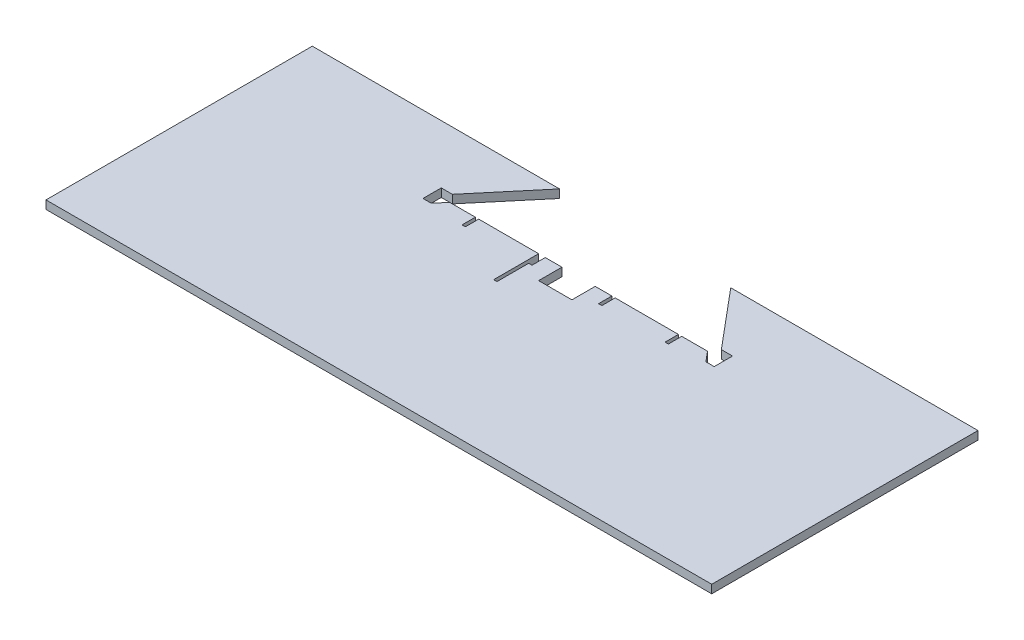
SolidWorks part; units mm, degrees
material "Depron"
ref_plane "Front Plane" through (0, 0, 0) normal (0, 0, 1) x (1, 0, 0)
ref_plane "Top Plane" through (0, 0, 0) normal (0, 1, 0) x (1, 0, 0)
ref_plane "Right Plane" through (0, 0, 0) normal (1, 0, 0) x (0, 0, -1)
sketch "Sketch1" plane through (0, 0, 0) normal (0, 1, 0) x (1, 0, 0)
  line L0 (32.6619, 101.6) -> (127, 101.6)
  line L1 (-127, 0) -> (127, 0)
  line L2 (-127, 0) -> (-127, 101.6)
  line L3 (-127, 101.6) -> (-32.6619, 101.6)
  line L4 (127, 0) -> (127, 101.6)
  line L5 (0, -898.4) -> (0, 49101.6) construction
  line L6 (-53.975, 76.2) -> (-32.6619, 101.6)
  line L7 (-53.975, 76.2) -> (53.975, 76.2)
  line L8 (53.975, 76.2) -> (32.6619, 101.6)
  line L9 (-1003.9539, 76.2) -> (48996.0461, 76.2) construction
  point P11 (0, 76.2)
  dimension "D1" = 101.6
  dimension "D2" = 254
  dimension "D4" = 107.95
  dimension "D6" = 25.4
extrude "Boss-Extrude1" add sketch "Sketch1" along normal blind 3.175
sketch "Sketch2" plane through (0, 3.175, 0) normal (0, 1, 0) x (-1, 0, 0)
  line L0 (0, 0) -> (0, -134.62) construction
  line L1 (127, 0) -> (-127, 0) construction
  line L2 (-53.975, -76.2) -> (53.975, -76.2) construction
  line L3 (39.37, -76.2) -> (38.1, -76.2)
  line L4 (39.37, -76.2) -> (39.37, -71.12)
  line L5 (39.37, -71.12) -> (38.1, -71.12)
  line L6 (38.1, -76.2) -> (38.1, -71.12)
  line L7 (13.97, -76.2) -> (12.7, -76.2)
  line L8 (-53.975, -76.2) -> (53.975, -76.2) construction
  line L9 (13.97, -71.12) -> (12.7, -71.12)
  line L10 (12.7, -76.2) -> (12.7, -71.12)
  line L11 (-12.7, -76.2) -> (-12.7, -71.12)
  line L12 (-13.97, -71.12) -> (-12.7, -71.12)
  line L13 (-13.97, -76.2) -> (-13.97, -71.12)
  line L14 (-13.97, -76.2) -> (-12.7, -76.2)
  line L15 (-38.1, -76.2) -> (-38.1, -71.12)
  line L16 (-39.37, -71.12) -> (-38.1, -71.12)
  line L17 (-39.37, -76.2) -> (-39.37, -71.12)
  line L18 (-39.37, -76.2) -> (-38.1, -76.2)
  line L19 (6.35, -76.2) -> (-6.35, -76.2)
  line L20 (13.97, -76.2) -> (15.24, -76.2)
  line L21 (13.97, -71.12) -> (13.97, -59.055)
  line L22 (13.97, -59.055) -> (15.24, -59.055)
  line L23 (15.24, -76.2) -> (15.24, -59.055)
  line L24 (6.35, -76.2) -> (6.35, -67.31)
  line L25 (6.35, -67.31) -> (-6.35, -67.31)
  line L26 (-6.35, -76.2) -> (-6.35, -67.31)
  line L27 (-53.975, -76.2) -> (-51.3109, -79.375)
  line L28 (52.3875, -80.01) -> (55.5625, -80.01) construction
  line L29 (52.3875, -80.01) -> (52.3875, -72.39) construction
  line L30 (52.3875, -72.39) -> (55.5625, -72.39)
  line L31 (55.5625, -80.01) -> (55.5625, -72.39) construction
  line L32 (52.3875, -80.01) -> (55.5625, -72.39) construction
  line L33 (52.3875, -72.39) -> (55.5625, -80.01) construction
  line L34 (-52.3875, -76.2) -> (-53.975, -76.2)
  line L35 (-52.3875, -72.39) -> (-49.1905, -76.2)
  line L36 (-52.3875, -72.39) -> (-55.5625, -72.39)
  line L37 (53.975, -76.2) -> (32.6619, -101.6) construction
  line L38 (53.975, -76.2) -> (51.3109, -79.375)
  line L39 (51.3109, -79.375) -> (55.5625, -79.375)
  line L40 (55.5625, -79.375) -> (55.5625, -72.39)
  line L41 (52.3875, -72.39) -> (49.1905, -76.2)
  line L42 (52.3875, -76.2) -> (53.975, -76.2)
  line L43 (-55.5625, -79.375) -> (-55.5625, -72.39)
  line L44 (-51.3109, -79.375) -> (-55.5625, -79.375)
  point P31 (0, -67.31)
  point P32 (53.975, -76.2)
  dimension "D1" = 1.27
  dimension "D2" = 5.08
  dimension "D3" = 1.27
  dimension "D4" = 5.08
  dimension "D5" = 1.27
  dimension "D6" = 17.145
  dimension "D7" = 12.7
  dimension "D8" = 38.1
  dimension "D9" = 12.7
  dimension "D10" = 8.89
  dimension "D11" = 3.175
  dimension "D12" = 7.62
  dimension "D13" = 3.175
ref_plane "Center Plane" through (0, 0, 0) normal (1, 0, 0) x (0, 0, -1)
sketch "Sketch3" plane through (0, 3.175, 0) normal (0, 1, 0) x (1, 0, 0)
  line L0 (-38.735, 71.12) -> (-38.735, 76.2)
  line L1 (-39.37, 71.12) -> (-38.1, 71.12) construction
  line L2 (-39.37, 76.2) -> (-38.1, 76.2) construction
  line L3 (-14.605, 76.2) -> (-14.605, 59.055)
  line L4 (-13.97, 76.2) -> (-15.24, 76.2) construction
  line L5 (-13.97, 59.055) -> (-15.24, 59.055) construction
  line L6 (-13.335, 71.12) -> (-13.335, 76.2)
  line L7 (-13.97, 71.12) -> (-12.7, 71.12) construction
  line L8 (-13.97, 76.2) -> (-12.7, 76.2) construction
  line L9 (-6.35, 76.2) -> (-6.35, 67.31)
  line L10 (-6.35, 67.31) -> (6.35, 67.31)
  line L11 (6.35, 67.31) -> (6.35, 76.2)
  line L12 (13.335, 71.12) -> (13.335, 76.2)
  line L13 (13.97, 71.12) -> (12.7, 71.12) construction
  line L14 (13.97, 76.2) -> (12.7, 76.2) construction
  line L15 (38.735, 71.12) -> (38.735, 76.2)
  line L16 (39.37, 71.12) -> (38.1, 71.12) construction
  line L17 (39.37, 76.2) -> (38.1, 76.2) construction
extrude "Cut-Extrude1" cut sketch "Sketch2" against normal up to surface (3.175 mm away)
